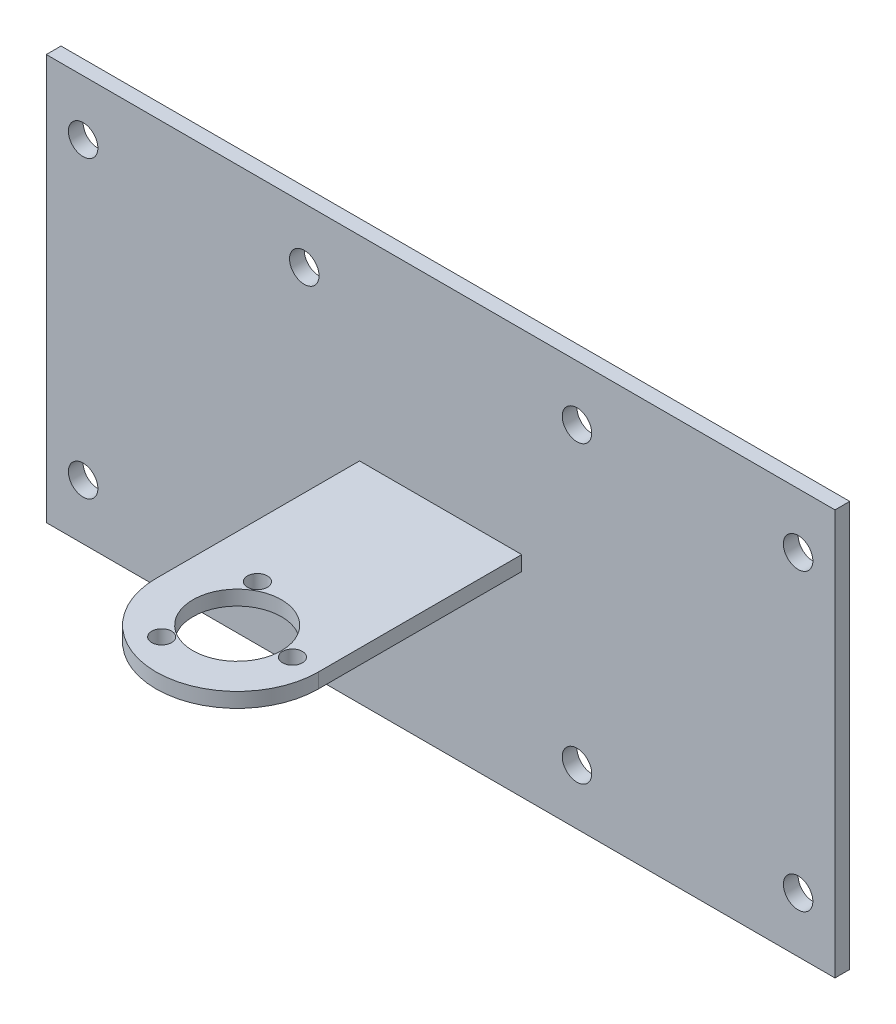
SolidWorks part; units mm, degrees
material "AISI 1045 Acero estirado en frío"
ref_plane "Front" through (0, 0, 0) normal (0, 0, 1) x (1, 0, 0)
ref_plane "Top" through (0, 0, 0) normal (0, 1, 0) x (1, 0, 0)
ref_plane "Right" through (0, 0, 0) normal (1, 0, 0) x (0, 0, -1)
sketch "Croquis1" plane through (0, 0, 0) normal (0, 0, 1) x (1, 0, 0)
  line L0 (0, 0) -> (0, 32.341) construction
  line L1 (-53.5, -27.5) -> (53.5, -27.5)
  line L2 (-53.5, -27.5) -> (-53.5, 27.5)
  line L3 (-53.5, 27.5) -> (53.5, 27.5)
  line L4 (53.5, -27.5) -> (53.5, 27.5)
  line L5 (-53.5, -27.5) -> (53.5, 27.5) construction
  line L6 (-53.5, 27.5) -> (53.5, -27.5) construction
  circle A0 centre (-48.5, 20) radius 2
  circle A1 centre (-48.5, -20) radius 2
  circle A2 centre (-18.5, 20) radius 2
  circle A3 centre (-18.5, -20) radius 2
  circle A4 centre (48.5, -20) radius 2
  circle A5 centre (18.5, -20) radius 2
  circle A6 centre (18.5, 20) radius 2
  circle A7 centre (48.5, 20) radius 2
  point P0 (0, 0)
  dimension "D3" = 7.5
  dimension "D4" = 5
  dimension "D6" = 4
  dimension "D7" = 30
  dimension "D1" = 107
  dimension "D2" = 55
  dimension "D5" = 7.5
extrude "Saliente-Extruir1" add sketch "Croquis1" along normal blind 2
sketch "Croquis2" plane through (0, 0, 2) normal (0, 0, -1) x (-1, 0, 0)
  line L1 (-11, -1) -> (11, -1)
  line L2 (-11, -1) -> (-11, 1)
  line L3 (-11, 1) -> (11, 1)
  line L4 (11, -1) -> (11, 1)
  line L5 (-11, -1) -> (11, 1) construction
  line L6 (-11, 1) -> (11, -1) construction
  point P0 (0, 0)
  dimension "D1" = 22
  dimension "D2" = 2
extrude "Saliente-Extruir2" add sketch "Croquis2" against normal blind 27.6
sketch "Croquis3" plane through (0, 1, 0) normal (0, 1, 0) x (1, 0, 0)
  line L0 (-11, -29.6) -> (11, -29.6) construction
  circle A1 centre (0, -29.6) radius 11
extrude "Saliente-Extruir3" add sketch "Croquis3" against normal up to surface (2 mm away) up to face at (0, -1, 15.8)
sketch "Croquis4" plane through (0, 1, 0) normal (0, 1, 0) x (1, 0, 0)
  circle A0 centre (0, -29.6) radius 6
  dimension "D1" = 12
extrude "Cortar-Extruir1" cut sketch "Croquis4" against normal blind 187.15
sketch "Croquis6" plane through (0, 1, 0) normal (0, 1, 0) x (1, 0, 0)
  line L0 (0, -29.6) -> (7.5, -29.6) construction
  circle A0 centre (7.5, -29.6) radius 1.35
  circle A1 centre (0, -29.6) radius 6 construction
  circle A2 centre (-3.75, -36.0952) radius 1.35
  circle A3 centre (-3.75, -23.1048) radius 1.35
  point P13 (0, -29.6)
  dimension "D1" = 2.7
  dimension "D2" = 7.5
  dimension "D3" = 3
extrude "Cortar-Extruir2" cut sketch "Croquis6" against normal blind 187.15
